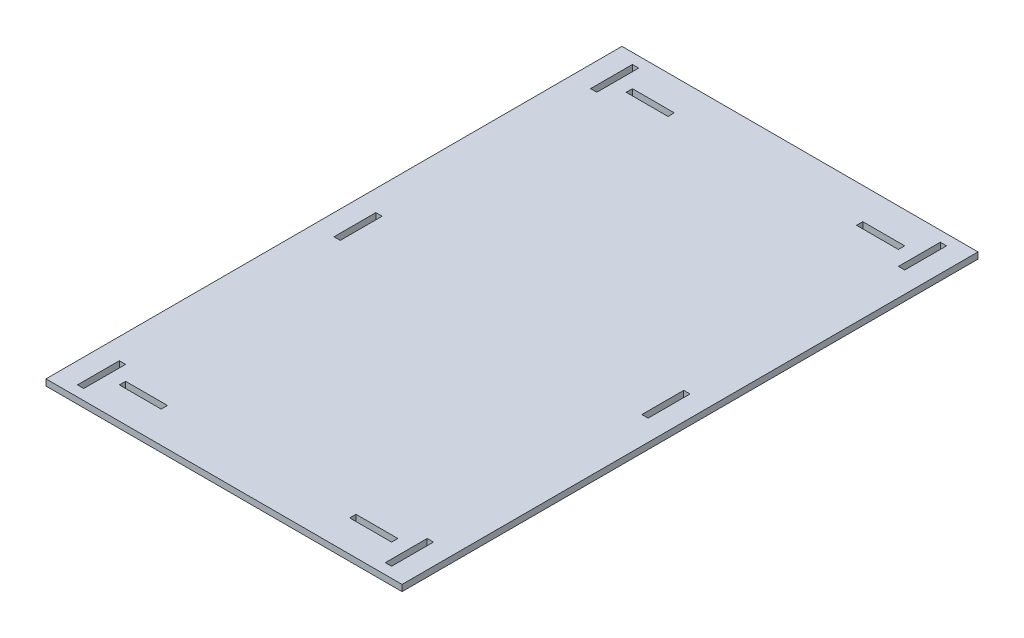
SolidWorks part; units mm, degrees
ref_plane "Front Plane" through (0, 0, 0) normal (0, 0, 1) x (1, 0, 0)
ref_plane "Top Plane" through (0, 0, 0) normal (0, 1, 0) x (1, 0, 0)
ref_plane "Right Plane" through (0, 0, 0) normal (1, 0, 0) x (0, 0, -1)
sketch "Sketch1" plane through (0, 0, 0) normal (0, 1, 0) x (1, 0, 0)
  line L1 (0, 0) -> (340, 0)
  line L2 (0, 0) -> (0, 550)
  line L3 (0, 550) -> (340, 550)
  line L4 (340, 0) -> (340, 550)
  point P5 (0, 0)
  dimension "D1" = 550
  dimension "D2" = 340
extrude "Boss-Extrude1" add sketch "Sketch1" along normal blind 6 contours L2 L3 L4 L1
sketch "Sketch2" plane through (0, 6, 0) normal (0, 1, 0) x (1, 0, 0)
  line L1 (20, 540) -> (26, 540)
  line L2 (20, 540) -> (20, 500)
  line L3 (20, 500) -> (26, 500)
  line L4 (26, 540) -> (26, 500)
  line L5 (0, 0) -> (0, 550) construction
  line L7 (0, 550) -> (340, 550) construction
  dimension "D1" = 40
  dimension "D2" = 6
  dimension "D3" = 20
  dimension "D4" = 10
extrude "Cut-Extrude1" cut sketch "Sketch2" against normal blind 6
pattern_linear "LPattern1" count 2 spacing 294 along (1, 0, 0) count 3 spacing 245 along (0, 0, 1) of "Cut-Extrude1"
sketch "Sketch3" plane through (0, 6, 0) normal (0, 1, 0) x (1, 0, 0)
  line L0 (340, 0) -> (340, 550) construction
  line L1 (300, 520) -> (260, 520)
  line L2 (300, 520) -> (300, 514)
  line L3 (300, 514) -> (260, 514)
  line L4 (260, 520) -> (260, 514)
  line L5 (0, 550) -> (340, 550) construction
  dimension "D1" = 40
  dimension "D2" = 6
  dimension "D3" = 40
  dimension "D4" = 30
extrude "Cut-Extrude2" cut sketch "Sketch3" against normal blind 10
pattern_linear "LPattern2" count 2 spacing 220 along (-1, 0, 0) count 2 spacing 484 along (0, 0, 1) of "Cut-Extrude2"
